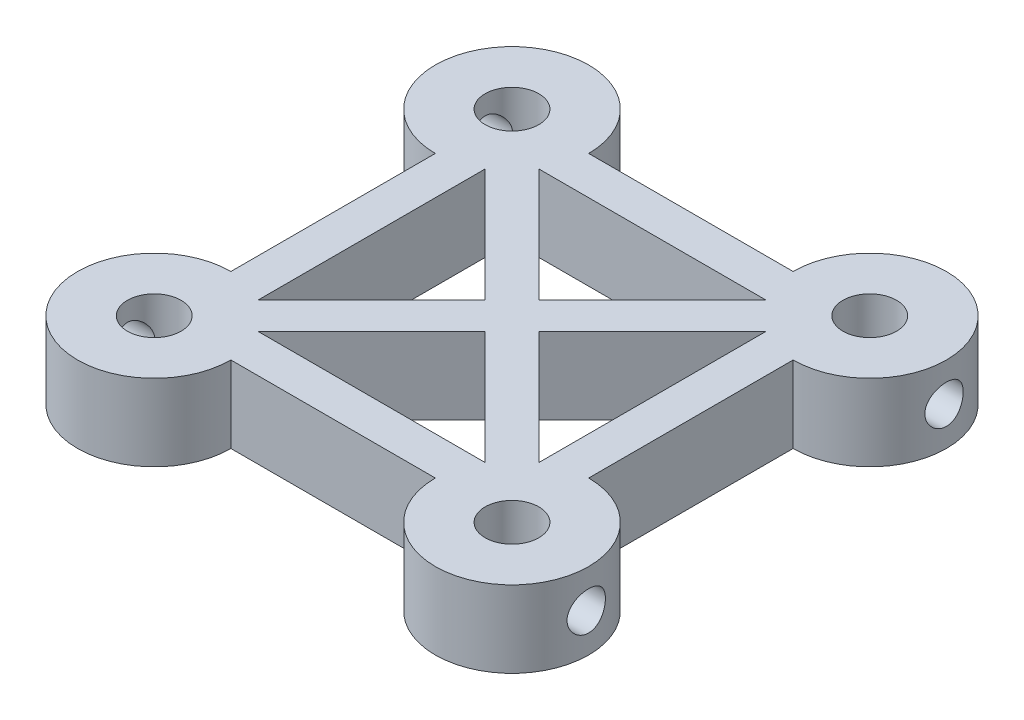
SolidWorks part; units mm, degrees
ref_plane "Front Plane" through (0, 0, 0) normal (0, 0, 1) x (1, 0, 0)
ref_plane "Top Plane" through (0, 0, 0) normal (0, 1, 0) x (1, 0, 0)
ref_plane "Right Plane" through (0, 0, 0) normal (1, 0, 0) x (0, 0, -1)
sketch "Sketch1" plane through (0, 0, 0) normal (0, 1, 0) x (1, 0, 0)
  line L0 (14, 28) -> (14, 0) construction
  line L1 (0, 0) -> (28, 0)
  line L2 (0, 0) -> (0, 28)
  line L3 (0, 28) -> (28, 28)
  line L4 (28, 0) -> (28, 28)
  line L5 (0, 14) -> (28, 14) construction
  point P9 (14, 14)
  dimension "D1" = 28
extrude "Boss-Extrude1" add sketch "Sketch1" along normal blind 6
sketch "Sketch2" plane through (0, 6, 0) normal (0, 1, 0) x (1, 0, 0)
  line L0 (14, 28) -> (14, -49972) construction
  line L1 (28, 28) -> (0, 28) construction
  line L2 (0, 14) -> (50000, 14) construction
  line L3 (0, 28) -> (0, 0) construction
  circle A0 centre (0, 28) radius 6
  circle A1 centre (28, 28) radius 6
  circle A2 centre (28, 0) radius 6
  circle A3 centre (0, 0) radius 6
  point P7 (14, 28)
  point P12 (0, 14)
  dimension "D1" = 12
extrude "Boss-Extrude2" add sketch "Sketch2" against normal up to surface (6 mm away) up to face at (14, 0, -14)
sketch "Sketch3" plane through (0, 6, 0) normal (0, 1, 0) x (1, 0, 0)
  line L0 (0, 0) -> (0, 28) construction
  line L1 (0, 28) -> (28, 28) construction
  line L2 (0, 0) -> (0, 28) construction
  line L3 (0, 28) -> (28, 28) construction
  line L4 (14, 28) -> (14, -49972) construction
  line L5 (0, 14) -> (50000, 14) construction
  circle A0 centre (0, 28) radius 2.1
  circle A1 centre (28, 28) radius 2.1
  circle A2 centre (28, 0) radius 2.1
  circle A3 centre (0, 0) radius 2.1
  point P6 (14, 28)
  point P9 (0, 14)
  dimension "D1" = 4.2
extrude "Cut-Extrude1" cut sketch "Sketch3" against normal through all
sketch "Sketch4" plane through (0, 6, 0) normal (0, 1, 0) x (1, 0, 0)
  line L0 (14, 28) -> (14, 0) construction
  line L1 (0, 14) -> (28, 14) construction
  line L2 (28, 0) -> (28, 28) construction
  line L3 (0, 0) -> (28, 0) construction
  line L4 (0, 0) -> (0, 28) construction
  line L5 (0, 28) -> (28, 28) construction
  line L6 (14, 28) -> (14, 0) construction
  line L7 (0, 14) -> (28, 14) construction
  line L8 (28, 0) -> (28, 28) construction
  line L9 (0, 0) -> (28, 0) construction
  line L10 (0, 0) -> (0, 28) construction
  line L11 (0, 28) -> (28, 28) construction
  line L12 (0, 28) -> (28, 0) construction
  line L13 (3, 25) -> (25, 25)
  line L14 (3, 25) -> (3, 3)
  line L15 (3, 3) -> (25, 3)
  line L16 (25, 25) -> (25, 3)
  line L17 (0, 0) -> (28, 28) construction
  line L18 (3, 22.8787) -> (11.8787, 14)
  line L19 (5.1213, 25) -> (14, 16.1213)
  line L20 (3, 5.1213) -> (11.8787, 14)
  line L21 (5.1213, 3) -> (14, 11.8787)
  line L22 (14, 16.1213) -> (22.8787, 25)
  line L23 (14, 11.8787) -> (22.8787, 3)
  line L24 (16.1213, 14) -> (25, 22.8787)
  line L25 (16.1213, 14) -> (25, 5.1213)
  point P12 (14, 25)
  point P13 (3, 14)
  dimension "D1" = 3
  dimension "D2" = 3
extrude "Cut-Extrude2" cut sketch "Sketch4" against normal blind 10 contours L14 L20 L18 | L19 L22 L13 | L24 L25 L16 | L23 L21 L15
sketch "Sketch5" plane through (28, 0, 0) normal (1, 0, 0) x (0, 0, -1)
  line L0 (28, 6) -> (28, 0) construction
  line L1 (0, 0) -> (0, 6) construction
  line L2 (28, 6) -> (28, 0) construction
  line L3 (0, 0) -> (0, 6) construction
  circle A0 centre (0, 3) radius 1.5
  circle A1 centre (28, 3) radius 1.5
  point P8 (0, 0)
  point P9 (0, 3)
  point P10 (0, 0)
  point P11 (28, 3)
  point P12 (0, 0)
  dimension "D1" = 3
sketch "Sketch6" plane through (0, 0, 0) normal (-1, 0, 0) x (0, 0, 1)
  circle A0 centre (-28, 3) radius 1.5 construction
  circle A1 centre (0, 3) radius 1.5 construction
  circle A2 centre (-28, 3) radius 1.5
  circle A3 centre (0, 3) radius 1.5
extrude "Cut-Extrude3" cut sketch "Sketch5" along normal blind 10
extrude "Cut-Extrude4" cut sketch "Sketch6" along normal blind 10
equation "\"TrackLength\"= 150"
equation "\"MarbleWidth\"= 13"
equation "\"MarbleTrackWidth\"= \"MarbleWidth\" - 1"
equation "\"TrackWidth\"= \"MarbleTrackWidth\" + ( 2 * 4 )"
equation "\"MarbleTrackLength\"= \"TrackLength\" - ( 2 * 8 )"
equation "\"MountWidth\"= \"TrackWidth\" + 8"
equation "\"D1@Sketch1\"= \"MountWidth\""
equation "\"RampDepth\"=6"
equation "\"RampAngle\"= 10"
equation "\"RampHeight\"= ( \"MountWidth\" * tan ( \"RampAngle\" ) ) + \"RampDepth\""
equation "\"MountWidth\"= \"TrackWidth\" + 10"
equation "\"MountLength\"=66.6651"
